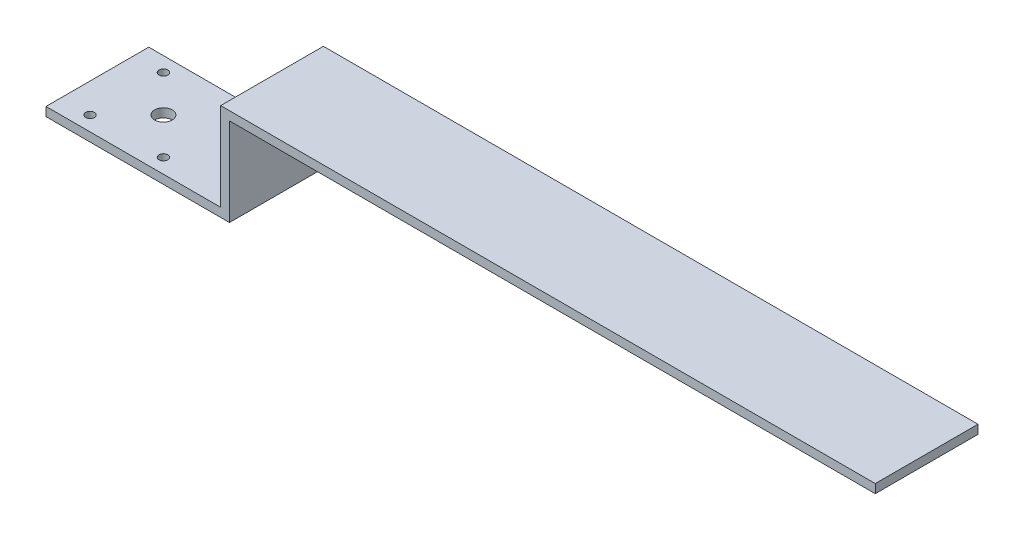
SolidWorks part; units mm, degrees
ref_plane "Front Plane" through (0, 0, 0) normal (0, 0, 1) x (1, 0, 0)
ref_plane "Top Plane" through (0, 0, 0) normal (0, 1, 0) x (1, 0, 0)
ref_plane "Right Plane" through (0, 0, 0) normal (1, 0, 0) x (0, 0, -1)
sketch "Sketch1" plane through (0, 0, 0) normal (0, 1, 0) x (1, 0, 0)
  line L0 (-31.25, 0) -> (0, 0) construction
  line L1 (-31.25, 17.5) -> (31.25, 17.5)
  line L2 (-31.25, 17.5) -> (-31.25, -17.5)
  line L3 (-31.25, -17.5) -> (31.25, -17.5)
  line L4 (31.25, 17.5) -> (31.25, -17.5)
  line L5 (-31.25, 17.5) -> (31.25, -17.5) construction
  line L6 (-31.25, -17.5) -> (31.25, 17.5) construction
  line L7 (3.75, 12.5) -> (-21.25, -12.5) construction
  circle A0 centre (-21.25, 12.5) radius 1.5
  circle A1 centre (-21.25, -12.5) radius 1.5
  circle A2 centre (3.75, 12.5) radius 1.5
  circle A3 centre (3.75, -12.5) radius 1.5
  circle A4 centre (-8.75, 0) radius 3
  point P0 (0, 0)
  dimension "D3" = 25
  dimension "D4" = 12.5
  dimension "D5" = 3
  dimension "D6" = 3
  dimension "D8" = 10
  dimension "D9" = 3
  dimension "D10" = 3
  dimension "D12" = 25
  dimension "D13" = 25
  dimension "D14" = 12.5
  dimension "D15" = 6
  dimension "D16" = 40
  dimension "D2" = 35
  dimension "D7" = 10
  dimension "D11" = 25
extrude "Boss-Extrude1" add sketch "Sketch1" along normal blind 3
sketch "Sketch3" plane through (0, 3, 0) normal (0, 1, 0) x (1, 0, 0)
  line L0 (-31.25, -17.5) -> (31.25, -17.5) construction
  line L1 (31.25, 17.5) -> (28.25, 17.5)
  line L2 (31.25, 17.5) -> (31.25, -17.5)
  line L3 (31.25, -17.5) -> (28.25, -17.5)
  line L4 (28.25, 17.5) -> (28.25, -17.5)
  dimension "D1" = 3
extrude "Boss-Extrude3" add sketch "Sketch3" along normal blind 30
sketch "Sketch4" plane through (31.25, 0, 0) normal (1, 0, 0) x (0, 0, -1)
  line L0 (17.5, 33) -> (17.5, 0) construction
  line L1 (-17.5, 33) -> (17.5, 33)
  line L2 (-17.5, 33) -> (-17.5, 30)
  line L3 (-17.5, 30) -> (17.5, 30)
  line L4 (17.5, 33) -> (17.5, 30)
  dimension "D1" = 3
extrude "Boss-Extrude4" add sketch "Sketch4" along normal blind 220
